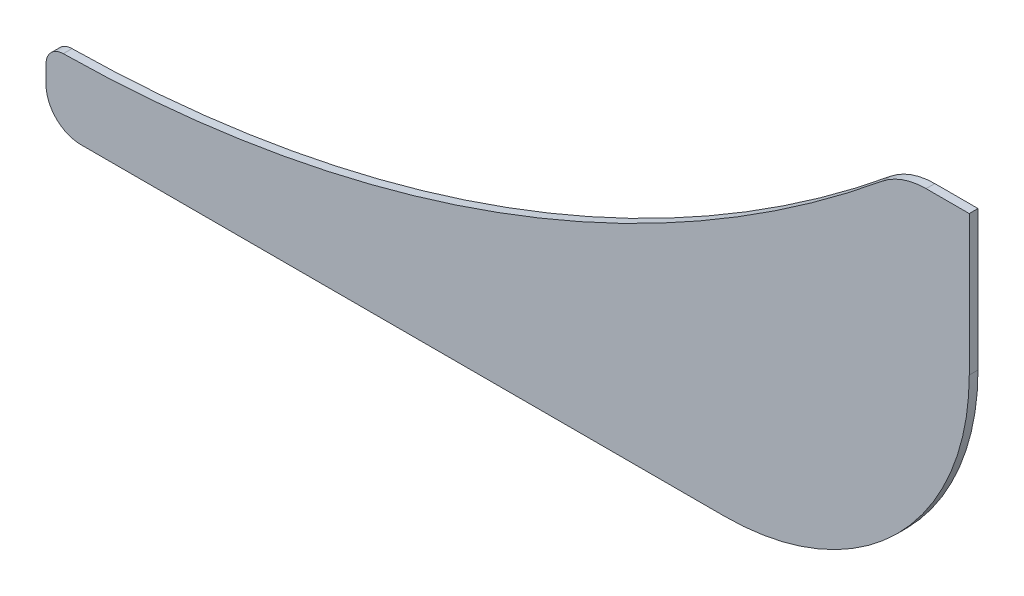
SolidWorks part; units mm, degrees
ref_plane "Front Plane" through (0, 0, 0) normal (0, 0, 1) x (1, 0, 0)
ref_plane "Top Plane" through (0, 0, 0) normal (0, 1, 0) x (1, 0, 0)
ref_plane "Right Plane" through (0, 0, 0) normal (1, 0, 0) x (0, 0, -1)
sketch "Sketch1" plane through (0, 0, 0) normal (0, 0, 1) x (1, 0, 0)
  line L15 (771.9038, 126.6023) -> (771.9038, 164.7023)
  line L17 (-107.95, -236.22) -> (-107.95, -261.62)
  line L20 (0, 0) -> (82.8917, 0) construction
  line L21 (-107.95, -236.22) -> (-282.5077, -236.22) construction
  line L22 (771.9038, 126.6023) -> (907.5478, 126.6023) construction
  line L25 (562.8488, -109.22) -> (562.8488, -7.62)
  line L26 (-82.55, -287.02) -> (385.0488, -287.02)
  line L27 (312.4515, -206.6231) -> (466.4308, -117.7231) construction
  line L28 (443.2209, -118.9957) -> (537.4488, -33.8481) construction
  line L29 (562.8488, -7.62) -> (531.4835, -7.62)
  line L40 (361.6164, -231.6548) -> (133.988, -252.7091) construction
  line L41 (157.3315, -273.5734) -> (-70.4948, -254.7805) construction
  arc A5 (-107.95, -261.62) -> (-82.55, -287.02) centre (-82.55, -261.62) ccw
  arc A6 (-107.95, -236.22) -> (499.2773, -19.1338) centre (-107.95, 721.5827) ccw
  arc A7 (562.8488, -109.22) -> (385.0488, -287.02) centre (385.0488, -109.22) cw
  arc A8 (531.4835, -7.62) -> (499.2773, -19.1338) centre (531.4835, -58.42) ccw
  spline S1 degree 3 poles (155.9851, -273.8364) (157.6707, -273.5362) (155.9614, -273.6091) (154.545, -273.5632) (151.109, -273.588) (146.869, -273.5671) (141.3082, -273.5292) (134.7264, -273.4415) (127.1182, -273.2946) (118.6055, -273.0609) (109.2803, -272.7261) (99.2556, -272.2668) (88.6466, -271.6729) (77.573, -270.9316) (66.1571, -270.0445) (54.5244, -269.0143) (42.7988, -267.8665) (31.1129, -266.6039) (19.6424, -265.3305) (8.5257, -263.8763) (-2.1301, -262.2171) (-12.2969, -260.4475) (-21.892, -258.6332) (-30.8295, -256.8671) (-39.0349, -255.237) (-46.4259, -253.8191) (-52.9324, -252.6861) (-58.4856, -251.9178) (-63.0313, -251.5394) (-66.5319, -251.6451) (-69.0472, -252.1302) (-70.6657, -253.5459) (-70.4472, -255.6917) (-68.9062, -257.778) (-66.3025, -260.229) (-62.4745, -262.9527) (-57.4718, -265.9263) (-51.2992, -269.0205) (-44.0206, -272.1448) (-35.7023, -275.171) (-26.4373, -277.9912) (-16.3291, -280.4924) (-5.4995, -282.5807) (5.9153, -284.1891) (17.7142, -285.2159) (29.7294, -285.7521) (41.8149, -286.0007) (53.9003, -285.9233) (65.8505, -285.5546) (77.5302, -284.9222) (88.8084, -284.06) (99.5605, -283.0113) (109.6699, -281.8268) (119.0235, -280.5542) (127.5233, -279.2575) (135.0819, -277.9817) (141.5945, -276.7938) (147.0755, -275.7324) (151.2398, -274.8709) (154.6131, -274.1873) (155.9851, -273.8364) (157.6707, -273.5362) (155.9614, -273.6091) knots -0.012273 -0.005484 -0.001375 0 0.001366 0.005489 0.012269 0.02165 0.033497 0.04769 0.06403 0.082338 0.102396 0.123959 0.146791 0.170641 0.19524 0.220332 0.245646 0.27091 0.295825 0.31977 0.342911 0.365083 0.386049 0.405629 0.423597 0.43978 0.453966 0.466008 0.475784 0.483219 0.48846 0.492078 0.495706 0.500976 0.508553 0.518608 0.53108 0.545907 0.56292 0.581928 0.60273 0.625094 0.648778 0.673537 0.699099 0.724814 0.750772 0.776731 0.802428 0.827555 0.851851 0.875071 0.896936 0.917223 0.935694 0.952169 0.966419 0.978318 0.987727 0.994516 0.998625 1 1.001366 1.005489 1.012269 only from (157.3315, -273.5734) to (157.3315, -273.5734) construction
  spline S3 degree 3 poles (360.3362, -232.1476) (361.944, -231.5594) (360.2733, -231.9279) (358.8705, -232.1286) (355.491, -232.7497) (351.3118, -233.4654) (345.8288, -234.3937) (339.3319, -235.4503) (331.8137, -236.6267) (323.3898, -237.8749) (314.1481, -239.1645) (304.196, -240.4529) (293.645, -241.7102) (282.6109, -242.9031) (271.2144, -244.0118) (259.5796, -245.0173) (247.8327, -245.923) (236.1052, -246.7089) (224.5878, -247.4466) (213.3874, -247.9449) (202.6055, -248.1613) (192.2857, -248.184) (182.5214, -248.0635) (173.413, -247.8762) (165.0492, -247.6957) (157.5243, -247.5827) (150.9198, -247.5968) (145.3176, -247.8045) (140.7752, -248.2212) (137.3462, -248.9332) (134.9534, -249.8477) (133.6053, -251.5229) (134.1931, -253.5982) (136.0729, -255.3852) (139.0627, -257.3468) (143.3055, -259.3644) (148.7486, -261.4241) (155.3647, -263.3995) (163.0752, -265.2124) (171.7927, -266.7481) (181.4066, -267.9166) (191.7956, -268.6246) (202.8233, -268.8006) (214.344, -268.4024) (226.142, -267.3648) (238.0677, -265.8064) (250.0128, -263.9526) (261.9011, -261.7778) (273.6057, -259.3395) (284.9982, -256.6886) (295.9553, -253.8811) (306.362, -250.9812) (316.1121, -248.0592) (325.1026, -245.1817) (333.2481, -242.4287) (340.4703, -239.8598) (346.6777, -237.559) (351.8912, -235.562) (355.8426, -233.9905) (359.046, -232.7314) (360.3362, -232.1476) (361.944, -231.5594) (360.2733, -231.9279) knots -0.012273 -0.005484 -0.001375 0 0.001366 0.005489 0.012269 0.02165 0.033497 0.04769 0.06403 0.082338 0.102396 0.123959 0.146791 0.170641 0.19524 0.220332 0.245646 0.27091 0.295825 0.31977 0.342911 0.365083 0.386049 0.405629 0.423597 0.43978 0.453966 0.466008 0.475784 0.483219 0.48846 0.492078 0.495706 0.500976 0.508553 0.518608 0.53108 0.545907 0.56292 0.581928 0.60273 0.625094 0.648778 0.673537 0.699099 0.724814 0.750772 0.776731 0.802428 0.827555 0.851851 0.875071 0.896936 0.917223 0.935694 0.952169 0.966419 0.978318 0.987727 0.994516 0.998625 1 1.001366 1.005489 1.012269 only from (361.6164, -231.6548) to (361.6164, -231.6548) construction
  spline S8 degree 3 poles (155.9851, -273.8364) (157.6707, -273.5362) (155.9614, -273.6091) (154.545, -273.5632) (151.109, -273.588) (146.869, -273.5671) (141.3082, -273.5292) (134.7264, -273.4415) (127.1182, -273.2946) (118.6055, -273.0609) (109.2803, -272.7261) (99.2556, -272.2668) (88.6466, -271.6729) (77.573, -270.9316) (66.1571, -270.0445) (54.5244, -269.0143) (42.7988, -267.8665) (31.1129, -266.6039) (19.6424, -265.3305) (8.5257, -263.8763) (-2.1301, -262.2171) (-12.2969, -260.4475) (-21.892, -258.6332) (-30.8295, -256.8671) (-39.0349, -255.237) (-46.4259, -253.8191) (-52.9324, -252.6861) (-58.4856, -251.9178) (-63.0313, -251.5394) (-66.5319, -251.6451) (-69.0472, -252.1302) (-70.6657, -253.5459) (-70.4472, -255.6917) (-68.9062, -257.778) (-66.3025, -260.229) (-62.4745, -262.9527) (-57.4718, -265.9263) (-51.2992, -269.0205) (-44.0206, -272.1448) (-35.7023, -275.171) (-26.4373, -277.9912) (-16.3291, -280.4924) (-5.4995, -282.5807) (5.9153, -284.1891) (17.7142, -285.2159) (29.7294, -285.7521) (41.8149, -286.0007) (53.9003, -285.9233) (65.8505, -285.5546) (77.5302, -284.9222) (88.8084, -284.06) (99.5605, -283.0113) (109.6699, -281.8268) (119.0235, -280.5542) (127.5233, -279.2575) (135.0819, -277.9817) (141.5945, -276.7938) (147.0755, -275.7324) (151.2398, -274.8709) (154.6131, -274.1873) (155.9851, -273.8364) (157.6707, -273.5362) (155.9614, -273.6091) knots -0.012273 -0.005484 -0.001375 0 0.001366 0.005489 0.012269 0.02165 0.033497 0.04769 0.06403 0.082338 0.102396 0.123959 0.146791 0.170641 0.19524 0.220332 0.245646 0.27091 0.295825 0.31977 0.342911 0.365083 0.386049 0.405629 0.423597 0.43978 0.453966 0.466008 0.475784 0.483219 0.48846 0.492078 0.495706 0.500976 0.508553 0.518608 0.53108 0.545907 0.56292 0.581928 0.60273 0.625094 0.648778 0.673537 0.699099 0.724814 0.750772 0.776731 0.802428 0.827555 0.851851 0.875071 0.896936 0.917223 0.935694 0.952169 0.966419 0.978318 0.987727 0.994516 0.998625 1 1.001366 1.005489 1.012269 only from (157.3315, -273.5734) to (157.3315, -273.5734) construction
  point P19 (562.8488, -287.02)
  point P39 (157.3315, -273.5734)
  dimension "D2" = 25.4
  dimension "D3" = 25.4
  dimension "D6" = 127
  dimension "D10" = 177.8
  dimension "D11" = 50.8
  dimension "D13" = 38.1
  dimension "D14" = 25.4
  dimension "D4" = 279.4
  dimension "D5" = 287.02
  dimension "D7" = 177.8
  dimension "D8" = 107.95
extrude "Boss-Extrude1" add sketch "Sketch1" along normal blind 6.35
fillet "Fillet1" radius 12.7 1 edges at (-107.95, -236.22, 3.175)
